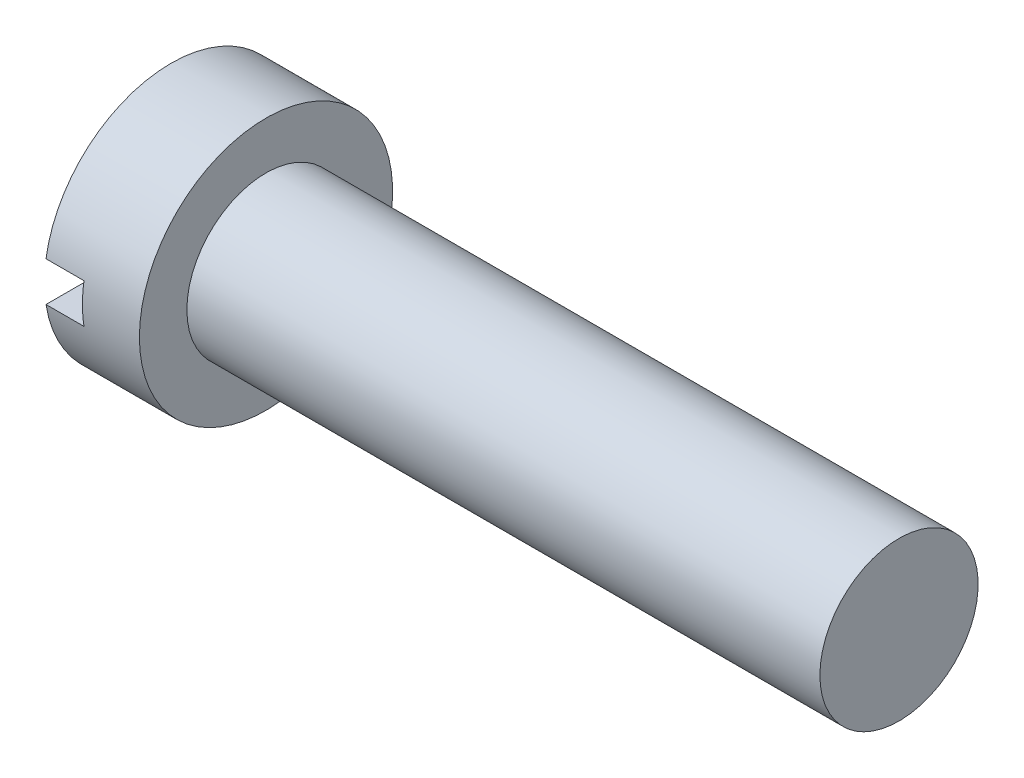
SolidWorks part; units mm, degrees
ref_plane "Plane1" through (0, 0, 0) normal (0, 0, 1) x (1, 0, 0)
ref_plane "Plane2" through (0, 0, 0) normal (0, 1, 0) x (1, 0, 0)
ref_plane "Plane3" through (0, 0, 0) normal (1, 0, 0) x (0, 0, -1)
sketch "BodySke" plane through (0, 0, 0) normal (0, 0, 1) x (1, 0, 0)
  line L0 (6, 5) -> (6, 8)
  line L1 (0, 0) -> (0, 8)
  line L2 (-25.4, 0) -> (127, 0) construction
  line L3 (46, 0) -> (0, 0)
  line L4 (6, 5) -> (46, 5)
  line L5 (46, 5) -> (46, 0)
  line L6 (0, 8) -> (6, 8)
  line L9 (7.5, 6.5875) -> (7.5, -2.9375) construction
  line L10 (26, 6.35) -> (26, -3.175) construction
revolve "Base-Revolve" add sketch "BodySke" angle 360 about L2
cosmetic thread "ThreadCosmetic" parameters "Thread_length"=20, "Thread_minor"=8.377
sketch "Sketch2" plane through (0, 0, 0) normal (1, 0, 0) x (0, 0, -1)
  line L0 (8, -1.25) -> (-8, -1.25)
  line L1 (8, -1.25) -> (8, 1.25)
  line L2 (-8, 1.25) -> (8, 1.25)
  line L3 (-8, 1.25) -> (-8, -1.25)
extrude "Slot" cut sketch "Sketch2" along normal blind 2.4
equation "\"D1@Sketch2\" = \"Head_dia@BodySke\""
equation "\"D2@Sketch2\" = \"D1@Sketch2\" / 2"
equation "\"D3@Sketch2\" = \"Slot_width@Sketch2\" / 2"
equation "\"Thread_length@ThreadCosmetic\" = ((sgn( (\"Length@BodySke\" - \"Advance@BodySke\" * 2.0 ) - \"Thread_nom@BodySke\" )-1)*( (\"Length@BodySke\" - \"Advance@BodySke\"  * 2.0) - \"Thread_nom@BodySke\" ))/-2+ \"Thread_nom@BodySke\""
